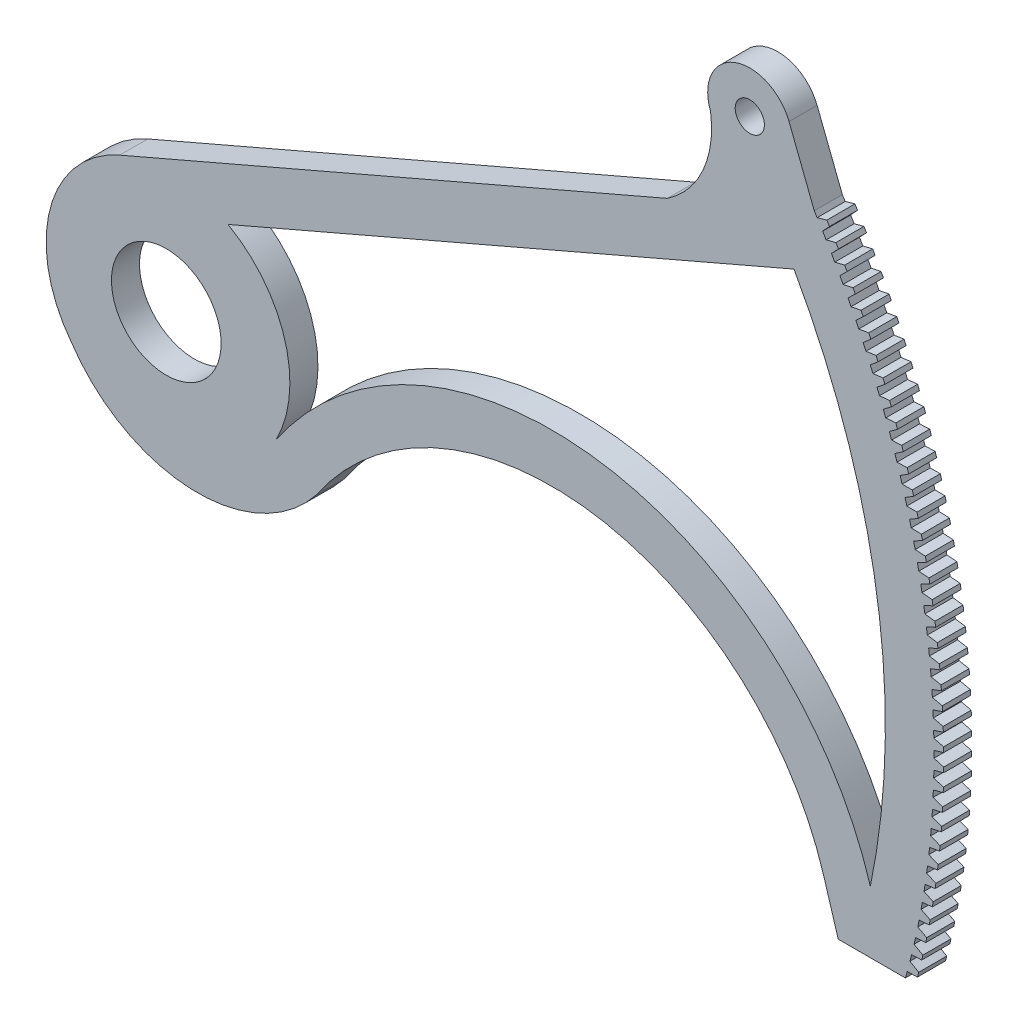
SolidWorks part; units mm, degrees
material "6061-T6 (SS)"
ref_plane "Front Plane" through (0, 0, 0) normal (0, 0, 1) x (1, 0, 0)
ref_plane "Top Plane" through (0, 0, 0) normal (0, 1, 0) x (1, 0, 0)
ref_plane "Right Plane" through (0, 0, 0) normal (1, 0, 0) x (0, 0, -1)
ref_plane "Plane1" through (0, 0, 0) normal (0, 0, -1) x (-1, 0, 0)
sketch "Sketch1" plane through (0, 0, 0) normal (0, 0, -1) x (-1, 0, 0)
  line L0 (-142.0413, 79.4124) -> (-13.9816, 24.1366)
  line L1 (10.5395, 25.4586) -> (-113.3545, 78.9363)
  line L2 (-140.913, 107.7805) -> (-146.6332, 93.133)
  line L3 (-147.2772, 92.1112) -> (-149.484, 92.7424)
  line L4 (-149.484, 92.7424) -> (-150.0769, 91.7799)
  line L5 (-150.0769, 91.7799) -> (-148.5214, 90.0913)
  line L6 (-149.3115, 88.7756) -> (-151.5321, 89.3569)
  line L7 (-151.5321, 89.3569) -> (-152.1031, 88.3814)
  line L8 (-152.1031, 88.3814) -> (-150.51, 86.7281)
  line L9 (-151.2704, 85.395) -> (-153.5034, 85.9263)
  line L10 (-153.5034, 85.9263) -> (-154.0524, 84.9381)
  line L11 (-154.0524, 84.9381) -> (-152.4225, 83.3211)
  line L12 (-153.1527, 81.9712) -> (-155.3971, 82.4521)
  line L13 (-155.3971, 82.4521) -> (-155.9237, 81.4519)
  line L14 (-155.9237, 81.4519) -> (-154.2579, 79.872)
  line L15 (-154.9576, 78.506) -> (-157.2122, 78.9363)
  line L16 (-157.2122, 78.9363) -> (-157.7162, 77.9245)
  line L17 (-157.7162, 77.9245) -> (-156.0153, 76.3824)
  line L18 (-156.684, 75.001) -> (-158.9478, 75.3805)
  line L19 (-158.9478, 75.3805) -> (-159.4289, 74.3576)
  line L20 (-159.4289, 74.3576) -> (-157.6937, 72.8542)
  line L21 (-158.3312, 71.4581) -> (-160.6029, 71.7866)
  line L22 (-160.6029, 71.7866) -> (-161.0609, 70.7532)
  line L23 (-161.0609, 70.7532) -> (-159.2924, 69.2891)
  line L24 (-159.8983, 67.8791) -> (-162.1768, 68.1564)
  line L25 (-162.1768, 68.1564) -> (-162.6115, 67.1129)
  line L26 (-162.6115, 67.1129) -> (-160.8104, 65.689)
  line L27 (-161.3845, 64.2657) -> (-163.6687, 64.4917)
  line L28 (-163.6687, 64.4917) -> (-164.0797, 63.4387)
  line L29 (-164.0797, 63.4387) -> (-162.2471, 62.0557)
  line L30 (-162.7891, 60.6198) -> (-165.0778, 60.7944)
  line L31 (-165.0778, 60.7944) -> (-165.465, 59.7324)
  line L32 (-165.465, 59.7324) -> (-163.6018, 58.3909)
  line L33 (-164.1113, 56.9433) -> (-166.4033, 57.0663)
  line L34 (-166.4033, 57.0663) -> (-166.7666, 55.9959)
  line L35 (-166.7666, 55.9959) -> (-164.8736, 54.6967)
  line L36 (-165.3504, 53.2379) -> (-167.6447, 53.3093)
  line L37 (-167.6447, 53.3093) -> (-167.9838, 52.231)
  line L38 (-167.9838, 52.231) -> (-166.0621, 50.9747)
  line L39 (-166.506, 49.5056) -> (-168.8012, 49.5254)
  line L40 (-168.8012, 49.5254) -> (-169.116, 48.4397)
  line L41 (-169.116, 48.4397) -> (-167.1665, 47.227)
  line L42 (-167.5773, 45.7482) -> (-169.8724, 45.7164)
  line L43 (-169.8724, 45.7164) -> (-170.1627, 44.624)
  line L44 (-170.1627, 44.624) -> (-168.1864, 43.4553)
  line L45 (-168.5638, 41.9677) -> (-170.8576, 41.8843)
  line L46 (-170.8576, 41.8843) -> (-171.1232, 40.7856)
  line L47 (-171.1232, 40.7856) -> (-169.1212, 39.6617)
  line L48 (-169.465, 38.166) -> (-171.7564, 38.0311)
  line L49 (-171.7564, 38.0311) -> (-171.9972, 36.9266)
  line L50 (-171.9972, 36.9266) -> (-169.9705, 35.8481)
  line L51 (-170.2805, 34.345) -> (-172.5683, 34.1585)
  line L52 (-172.5683, 34.1585) -> (-172.7842, 33.0489)
  line L53 (-172.7842, 33.0489) -> (-170.7337, 32.0162)
  line L54 (-171.0099, 30.5066) -> (-173.2929, 30.2687)
  line L55 (-173.2929, 30.2687) -> (-173.4838, 29.1546)
  line L56 (-173.4838, 29.1546) -> (-171.4106, 28.1682)
  line L57 (-171.6528, 26.6527) -> (-173.9298, 26.3636)
  line L58 (-173.9298, 26.3636) -> (-174.0956, 25.2454)
  line L59 (-174.0956, 25.2454) -> (-172.0008, 24.306)
  line L60 (-172.2088, 22.7854) -> (-174.4788, 22.4451)
  line L61 (-174.4788, 22.4451) -> (-174.6194, 21.3235)
  line L62 (-174.6194, 21.3235) -> (-172.5039, 20.4314)
  line L63 (-172.6777, 18.9066) -> (-174.9394, 18.5153)
  line L64 (-174.9394, 18.5153) -> (-175.0548, 17.3908)
  line L65 (-175.0548, 17.3908) -> (-172.9198, 16.5465)
  line L66 (-173.0592, 15.0182) -> (-175.3116, 14.5761)
  line L67 (-175.3116, 14.5761) -> (-175.4017, 13.4493)
  line L68 (-175.4017, 13.4493) -> (-173.2482, 12.6533)
  line L69 (-173.3532, 11.1222) -> (-175.5951, 10.6296)
  line L70 (-175.5951, 10.6296) -> (-175.6598, 9.501)
  line L71 (-175.6598, 9.501) -> (-173.4889, 8.7536)
  line L72 (-173.5595, 7.2205) -> (-175.7897, 6.6776)
  line L73 (-175.7897, 6.6776) -> (-175.829, 5.5479)
  line L74 (-175.829, 5.5479) -> (-173.6419, 4.8495)
  line L75 (-173.678, 3.3152) -> (-175.8955, 2.7223)
  line L76 (-175.8955, 2.7223) -> (-175.9093, 1.592)
  line L77 (-175.9093, 1.592) -> (-173.7071, 0.943)
  line L78 (-173.7086, -0.5917) -> (-175.9122, -1.2344)
  line L79 (-175.9122, -1.2344) -> (-175.9006, -2.3647)
  line L80 (-175.9006, -2.3647) -> (-173.6844, -2.964)
  line L81 (-173.6514, -4.4984) -> (-175.8399, -5.1904)
  line L82 (-175.8399, -5.1904) -> (-175.803, -6.3202)
  line L83 (-175.803, -6.3202) -> (-173.5738, -6.8696)
  line L84 (-173.5063, -8.4028) -> (-175.6787, -9.1439)
  line L85 (-175.6787, -9.1439) -> (-175.6163, -10.2725)
  line L86 (-175.6163, -10.2725) -> (-173.3754, -10.7716)
  line L87 (-173.2734, -12.3029) -> (-175.4286, -13.0927)
  line L88 (-175.4286, -13.0927) -> (-175.3409, -14.2197)
  line L89 (-175.3409, -14.2197) -> (-173.0892, -14.6682)
  line L90 (-172.9529, -16.1969) -> (-175.0898, -17.0349)
  line L91 (-175.0898, -17.0349) -> (-174.9767, -18.1596)
  line L92 (-174.9767, -18.1596) -> (-172.7156, -18.5574)
  line L93 (-172.5449, -20.0826) -> (-174.6624, -20.9684)
  line L94 (-174.6624, -20.9684) -> (-174.524, -22.0903)
  line L95 (-174.524, -22.0903) -> (-172.2545, -22.4372)
  line L96 (-172.0495, -23.9582) -> (-174.1466, -24.8914)
  line L97 (-174.1466, -24.8914) -> (-173.9831, -26.0099)
  line L98 (-173.9831, -26.0099) -> (-171.7063, -26.3056)
  line L99 (-171.4672, -27.8216) -> (-173.5427, -28.8018)
  line L100 (-173.5427, -28.8018) -> (-173.3541, -29.9163)
  line L101 (-173.3541, -29.9163) -> (-171.0712, -30.1607)
  line L102 (-170.7981, -31.671) -> (-172.8511, -32.6976)
  line L103 (-172.8511, -32.6976) -> (-172.6374, -33.8076)
  line L104 (-172.6374, -33.8076) -> (-170.3496, -34.0006)
  line L105 (-170.0426, -35.5043) -> (-172.072, -36.5768)
  line L106 (-172.072, -36.5768) -> (-171.8334, -37.6818)
  line L107 (-171.8334, -37.6818) -> (-169.5418, -37.8233)
  line L108 (-169.2011, -39.3197) -> (-171.2058, -40.4376)
  line L109 (-171.2058, -40.4376) -> (-170.9424, -41.5369)
  line L110 (-170.9424, -41.5369) -> (-168.6483, -41.6268)
  line L111 (-168.2739, -43.1152) -> (-170.253, -44.2779)
  line L112 (-170.253, -44.2779) -> (-169.965, -45.371)
  line L113 (-169.965, -45.371) -> (-167.6694, -45.4093)
  line L114 (-167.2596, -46.8963) -> (-152.0541, -46.8963)
  line L115 (-152.0541, -46.8963) -> (-148.7673, -36.0992)
  circle A0 centre (0, 0) radius 12.4082
  arc A1 (-24.7896, -12.7313) -> (-159.3234, -32.8857) centre (-87.2604, -54.8232) ccw
  arc A2 (-159.3234, -32.8857) -> (-142.0413, 79.4124) centre (-0.3914, 0.1345) cw
  arc A3 (-13.9816, 24.1366) -> (-24.7896, -12.7313) centre (-0.3914, 0.1345) ccw
  circle A4 centre (-132.0406, 104.3157) radius 3.302
  arc A5 (-148.7673, -36.0992) -> (-33.9406, -18.8971) centre (-87.2604, -54.8232) cw
  arc A6 (-33.9406, -18.8971) -> (21.4871, -16.6622) centre (-7.0401, 2.3923) ccw
  arc A7 (21.4871, -16.6622) -> (10.5395, 25.4586) centre (-0.3914, 0.1345) ccw
  arc A8 (-113.3545, 78.9363) -> (-123.162, 100.8665) centre (-100.9286, 97.6515) cw
  arc A9 (-123.162, 100.8665) -> (-140.913, 107.7805) centre (-132.0406, 104.3157) ccw
  arc A10 (-146.6332, 93.133) -> (-147.2772, 92.1112) centre (0, 0) ccw
  arc A11 (-148.5214, 90.0913) -> (-149.3115, 88.7756) centre (0, 0) ccw
  arc A12 (-150.51, 86.7281) -> (-151.2704, 85.395) centre (0, 0) ccw
  arc A13 (-152.4225, 83.3211) -> (-153.1527, 81.9712) centre (0, 0) ccw
  arc A14 (-154.2579, 79.872) -> (-154.9576, 78.506) centre (0, 0) ccw
  arc A15 (-156.0153, 76.3824) -> (-156.684, 75.001) centre (0, 0) ccw
  arc A16 (-157.6937, 72.8542) -> (-158.3312, 71.4581) centre (0, 0) ccw
  arc A17 (-159.2924, 69.2891) -> (-159.8983, 67.8791) centre (0, 0) ccw
  arc A18 (-160.8104, 65.689) -> (-161.3845, 64.2657) centre (0, 0) ccw
  arc A19 (-162.2471, 62.0557) -> (-162.7891, 60.6198) centre (0, 0) ccw
  arc A20 (-163.6018, 58.3909) -> (-164.1113, 56.9433) centre (0, 0) ccw
  arc A21 (-164.8736, 54.6967) -> (-165.3504, 53.2379) centre (0, 0) ccw
  arc A22 (-166.0621, 50.9747) -> (-166.506, 49.5056) centre (0, 0) ccw
  arc A23 (-167.1665, 47.227) -> (-167.5773, 45.7482) centre (0, 0) ccw
  arc A24 (-168.1864, 43.4553) -> (-168.5638, 41.9677) centre (0, 0) ccw
  arc A25 (-169.1212, 39.6617) -> (-169.465, 38.166) centre (0, 0) ccw
  arc A26 (-169.9705, 35.8481) -> (-170.2805, 34.345) centre (0, 0) ccw
  arc A27 (-170.7337, 32.0162) -> (-171.0099, 30.5066) centre (0, 0) ccw
  arc A28 (-171.4106, 28.1682) -> (-171.6528, 26.6527) centre (0, 0) ccw
  arc A29 (-172.0008, 24.306) -> (-172.2088, 22.7854) centre (0, 0) ccw
  arc A30 (-172.5039, 20.4314) -> (-172.6777, 18.9066) centre (0, 0) ccw
  arc A31 (-172.9198, 16.5465) -> (-173.0592, 15.0182) centre (0, 0) ccw
  arc A32 (-173.2482, 12.6533) -> (-173.3532, 11.1222) centre (0, 0) ccw
  arc A33 (-173.4889, 8.7536) -> (-173.5595, 7.2205) centre (0, 0) ccw
  arc A34 (-173.6419, 4.8495) -> (-173.678, 3.3152) centre (0, 0) ccw
  arc A35 (-173.7071, 0.943) -> (-173.7086, -0.5917) centre (0, 0) ccw
  arc A36 (-173.6844, -2.964) -> (-173.6514, -4.4984) centre (0, 0) ccw
  arc A37 (-173.5738, -6.8696) -> (-173.5063, -8.4028) centre (0, 0) ccw
  arc A38 (-173.3754, -10.7716) -> (-173.2734, -12.3029) centre (0, 0) ccw
  arc A39 (-173.0892, -14.6682) -> (-172.9529, -16.1969) centre (0, 0) ccw
  arc A40 (-172.7156, -18.5574) -> (-172.5449, -20.0826) centre (0, 0) ccw
  arc A41 (-172.2545, -22.4372) -> (-172.0495, -23.9582) centre (0, 0) ccw
  arc A42 (-171.7063, -26.3056) -> (-171.4672, -27.8216) centre (0, 0) ccw
  arc A43 (-171.0712, -30.1607) -> (-170.7981, -31.671) centre (0, 0) ccw
  arc A44 (-170.3496, -34.0006) -> (-170.0426, -35.5043) centre (0, 0) ccw
  arc A45 (-169.5418, -37.8233) -> (-169.2011, -39.3197) centre (0, 0) ccw
  arc A46 (-168.6483, -41.6268) -> (-168.2739, -43.1152) centre (0, 0) ccw
  arc A47 (-167.6694, -45.4093) -> (-167.2596, -46.8963) centre (0, 0) ccw
extrude "Boss-Extrude1" add sketch "Sketch1" against normal blind 6.35
